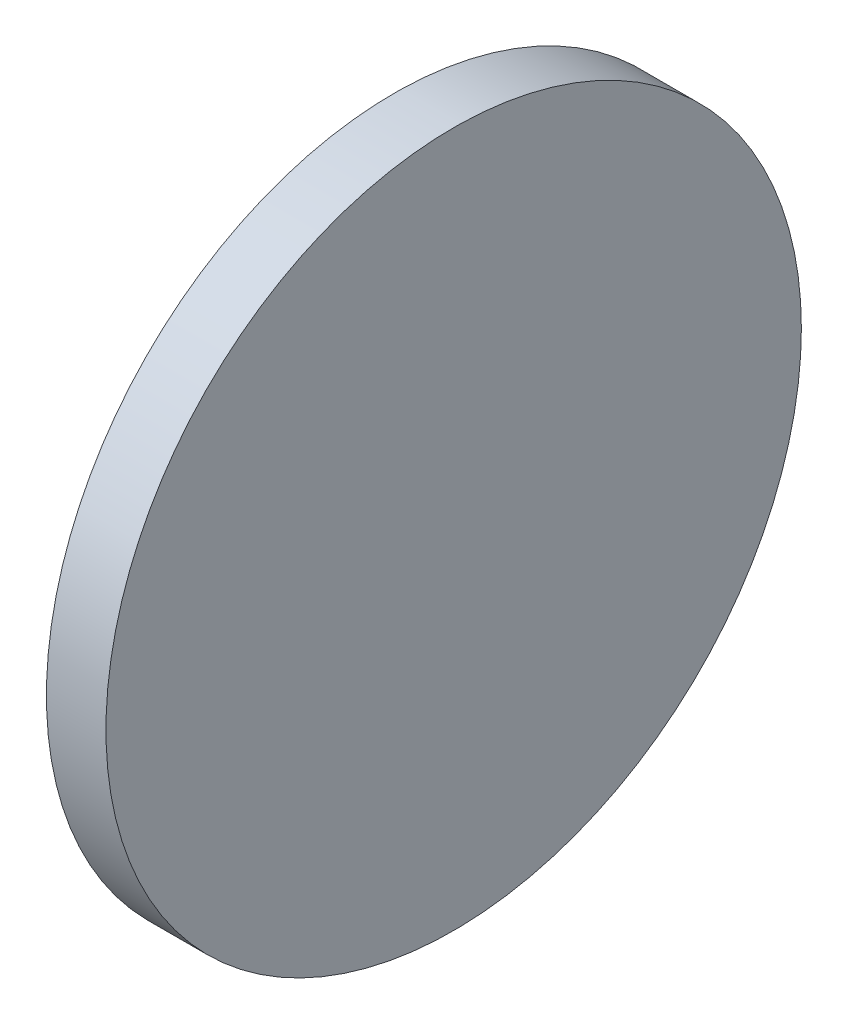
SolidWorks part; units mm, degrees
material "Настроенная пользователем пластмасса"
ref_plane "Спереди" through (0, 0, 0) normal (0, 0, 1) x (1, 0, 0)
ref_plane "Сверху" through (0, 0, 0) normal (0, 1, 0) x (1, 0, 0)
ref_plane "Справа" through (0, 0, 0) normal (1, 0, 0) x (0, 0, -1)
sketch "Эскиз1" plane through (0, 0, 0) normal (0, 1, 0) x (1, 0, 0)
  line L0 (0, 0) -> (-20.0597, 0) construction
  line L1 (-10.0299, 0) -> (-10.0299, 10)
  line L2 (-10.0299, 10) -> (-11.7422, 10)
  line L7 (-10.0299, 0) -> (-14.0299, 0)
  arc A2 (-11.7422, 10) -> (-14.0299, 0) centre (8.9701, 0) ccw
revolve "Повернуть1" add sketch "Эскиз1" angle 360 about L0
